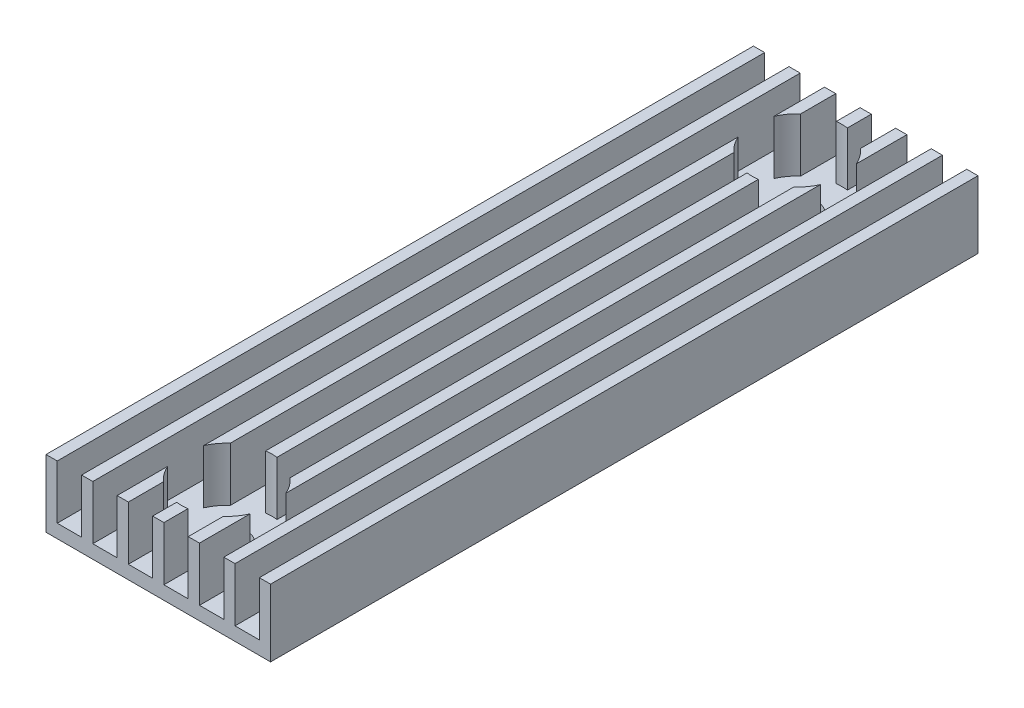
SolidWorks part; units mm, degrees
ref_plane "Спереди" through (0, 0, 0) normal (0, 0, 1) x (1, 0, 0)
ref_plane "Сверху" through (0, 0, 0) normal (0, 1, 0) x (1, 0, 0)
ref_plane "Справа" through (0, 0, 0) normal (1, 0, 0) x (0, 0, -1)
sketch "Sketch1" plane through (0, 0, 0) normal (0, 0, 1) x (1, 0, 0)
  line L0 (0, 0) -> (0, 36.8857) construction
  line L1 (-10, 6) -> (-10, 0)
  line L2 (-10, 0) -> (10, 0)
  line L3 (-10, 6) -> (-9, 6)
  line L4 (-9, 6) -> (-9, 1.2)
  line L5 (-9, 1.2) -> (-6.8333, 1.2)
  line L6 (-6.8333, 1.2) -> (-6.8333, 6)
  line L7 (-6.8333, 6) -> (-5.8333, 6)
  line L8 (-5.8333, 6) -> (-5.8333, 1.2)
  line L9 (-5.8333, 1.2) -> (-3.6667, 1.2)
  line L10 (-3.6667, 1.2) -> (-3.6667, 6)
  line L11 (-3.6667, 6) -> (-2.6667, 6)
  line L12 (-2.6667, 6) -> (-2.6667, 1.2)
  line L13 (-2.6667, 1.2) -> (-0.5, 1.2)
  line L14 (-0.5, 1.2) -> (-0.5, 6)
  line L15 (-0.5, 6) -> (0.5, 6)
  line L16 (0.5, 6) -> (0.5, 1.2)
  line L17 (0.5, 1.2) -> (2.6667, 1.2)
  line L18 (2.6667, 1.2) -> (2.6667, 6)
  line L19 (2.6667, 6) -> (3.6667, 6)
  line L20 (3.6667, 6) -> (3.6667, 1.2)
  line L21 (3.6667, 1.2) -> (5.8333, 1.2)
  line L22 (5.8333, 1.2) -> (5.8333, 6)
  line L23 (5.8333, 6) -> (6.8333, 6)
  line L24 (6.8333, 6) -> (6.8333, 1.2)
  line L25 (6.8333, 1.2) -> (9, 1.2)
  line L26 (9, 1.2) -> (9, 6)
  line L27 (9, 6) -> (10, 6)
  line L28 (10, 6) -> (10, 0)
  line L31 (10, 6) -> (10, 1.2) [skipped]
  line L32 (10, 1.2) -> (12.1667, 1.2) [skipped]
  line L33 (12.1667, 1.2) -> (12.1667, 6) [skipped]
  point P6 (-25.2206, 8.6884)
  point P7 (79.2076, 0)
  point P12 (8.501, 0)
  point P17 (-8.6939, 10.7108)
  point P22 (8.3582, 1.7094)
  point P27 (-5.8333, 6.3116)
  dimension "D2" = 6
  dimension "D3" = 20
  dimension "D4" = 1
  dimension "D5" = 1.2
  dimension "D1" = 7
extrude "Boss-Extrude1" add sketch "Sketch1" against normal blind 63
sketch "Sketch2" plane through (0, 0, 0) normal (0, 1, 0) x (1, 0, 0)
  line L0 (0, 0) -> (0, 63) construction
  line L1 (0.5, 63) -> (-0.5, 63) construction
  line L2 (0, 31.5) -> (16.4283, 31.5) construction
  circle A0 centre (0, 56.9) radius 1.75
  circle A1 centre (0, 6.1) radius 1.75
  dimension "D2" = 3.5
  dimension "D1" = 50.8
extrude "Cut-Extrude2" cut sketch "Sketch2" against normal through all and the other way through all
sketch "Sketch3" plane through (0, 0, 0) normal (0, 1, 0) x (1, 0, 0)
  circle A0 centre (0, 56.9) radius 4
  circle A1 centre (0, 6.1) radius 4
  dimension "D1" = 8
extrude "Cut-Extrude3" cut sketch "Sketch3" along normal blind 63 from vertex at 1.2 starting at point (-0.5, 1.2, -63)
